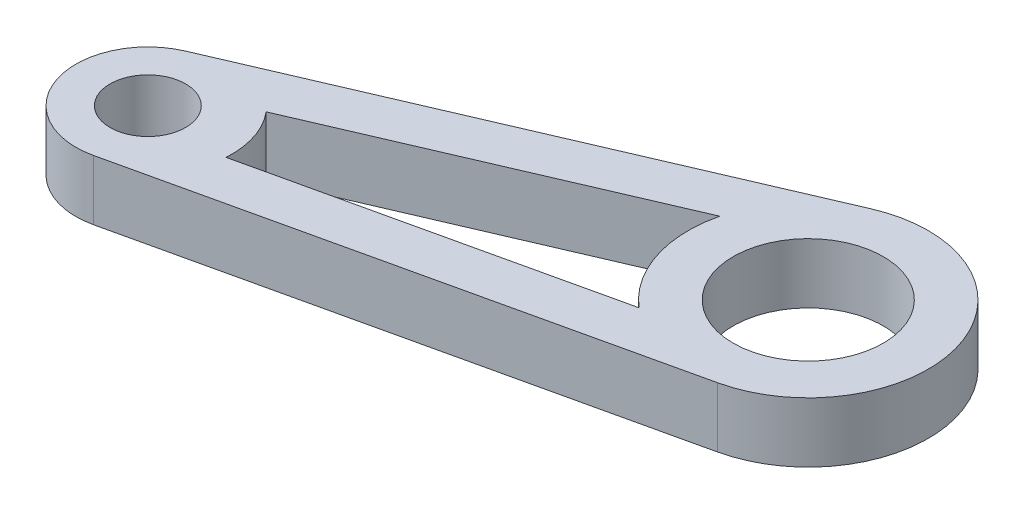
SolidWorks part; units mm, degrees
material "6061-T6 (SS)"
ref_plane "X-Y Datum" through (0, 0, 0) normal (0, 0, 1) x (1, 0, 0)
ref_plane "X-Z Datum" through (0, 0, 0) normal (0, 1, 0) x (1, 0, 0)
ref_plane "Y-Z Datum" through (0, 0, 0) normal (1, 0, 0) x (0, 0, -1)
sketch "Sketch1" plane through (0, 0, 0) normal (0, 1, 0) x (1, 0, 0)
  line L0 (1.4021, -6.1933) -> (-25.5213, -12.2885)
  line L1 (-2.5087, 5.8334) -> (-27.8678, -5.0724)
  line L2 (0, 0) -> (-26.3626, -8.5725) construction
  line L3 (-4.1134, -4.8376) -> (-21.9276, -8.8706)
  line L4 (-6.172, 1.4931) -> (-22.9511, -5.7229)
  circle A0 centre (0, 0) radius 3.9688
  circle A1 centre (-26.3626, -8.5725) radius 2
  arc A2 (-25.5213, -12.2885) -> (-27.8678, -5.0724) centre (-26.3626, -8.5725) cw
  arc A3 (-2.5087, 5.8334) -> (1.4021, -6.1933) centre (0, 0) cw
  arc A4 (-4.1134, -4.8376) -> (-6.172, 1.4931) centre (0, 0) cw
  arc A5 (-22.9511, -5.7229) -> (-21.9276, -8.8706) centre (-26.3626, -8.5725) cw
  dimension "D1" = 7.9375
  dimension "D2" = 8.5725
  dimension "D5" = 4
  dimension "D4" = 3.81
  dimension "D6" = 6.35
  dimension "D9" = 6.35
  dimension "D10" = 4.445
  dimension "D3" = 26.3626
  dimension "D7" = 2.54
  dimension "D8" = 2.54
  dimension "D11" = 27.7214
extrude "Boss-Extrude1" add sketch "Sketch1" against normal blind 3.175
